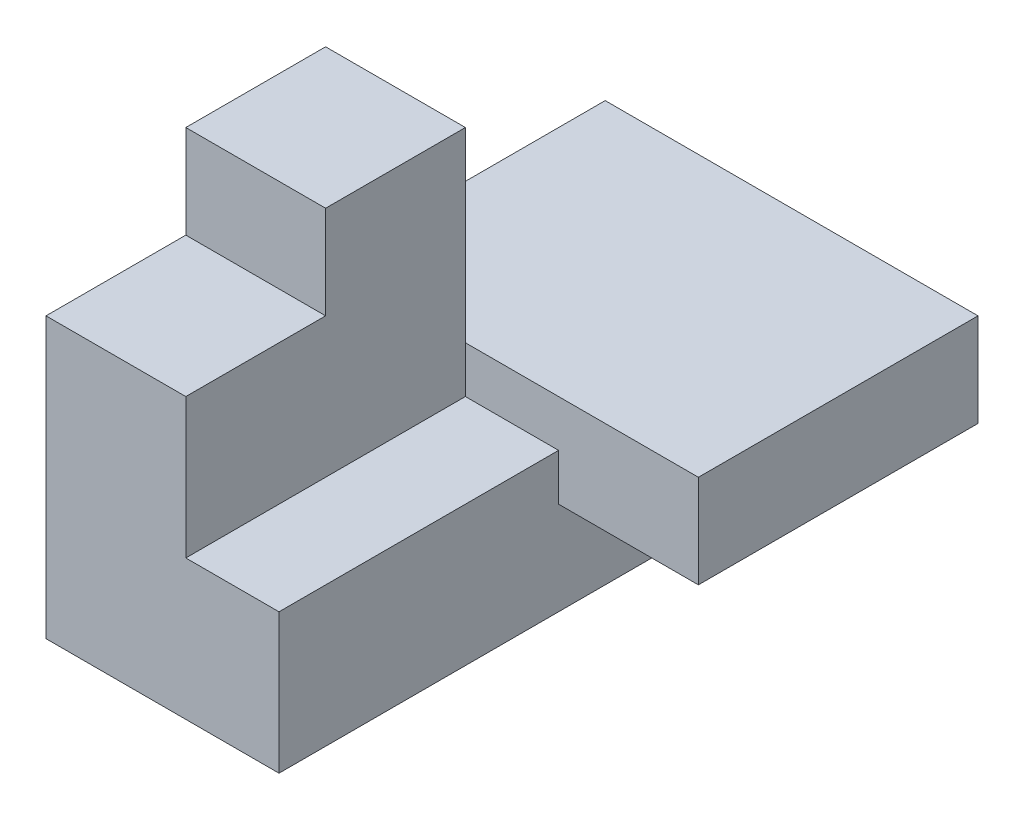
SolidWorks part; units mm, degrees
ref_plane "Front Plane" through (0, 0, 0) normal (0, 0, 1) x (1, 0, 0)
ref_plane "Top Plane" through (0, 0, 0) normal (0, 1, 0) x (1, 0, 0)
ref_plane "Right Plane" through (0, 0, 0) normal (1, 0, 0) x (0, 0, -1)
sketch "Sketch1" plane through (0, 0, 0) normal (0, 0, 1) x (1, 0, 0)
  line L1 (0, 0) -> (40, 0)
  line L2 (0, 0) -> (0, 40)
  line L3 (0, 40) -> (40, 40)
  line L4 (40, 0) -> (40, 40)
  dimension "D1" = 40
  dimension "D2" = 40
extrude "Boss-Extrude1" add sketch "Sketch1" along normal blind 60
sketch "Sketch2" plane through (0, 0, 60) normal (0, 0, 1) x (1, 0, 0)
  line L0 (0, 0) -> (40, 0) construction
  line L1 (40, 40) -> (20, 40)
  line L2 (40, 40) -> (40, 0)
  line L3 (40, 0) -> (20, 0)
  line L4 (20, 40) -> (20, 0)
extrude "Cut-Extrude1" cut sketch "Sketch2" against normal blind 30
sketch "Sketch3" plane through (40, 0, 0) normal (1, 0, 0) x (0, 0, -1)
  line L0 (0, 0) -> (0, 40) construction
  line L1 (-30, 0) -> (0, 0)
  line L2 (-30, 0) -> (-30, 20)
  line L3 (-30, 20) -> (0, 20)
  line L4 (0, 0) -> (0, 20)
sketch "Sketch4" plane through (0, 40, 0) normal (0, 1, 0) x (1, 0, 0)
  line L0 (0, -60) -> (0, 0) construction
  line L1 (40, 0) -> (0, 0)
  line L2 (40, 0) -> (40, -30)
  line L3 (40, -30) -> (0, -30)
  line L4 (0, 0) -> (0, -30)
extrude "Cut-Extrude2" cut sketch "Sketch4" against normal blind 20
sketch "Sketch5" plane through (40, 0, 0) normal (1, 0, 0) x (0, 0, -1)
  line L0 (-30, 0) -> (-30, 20) construction
  line L1 (0, 0) -> (-30, 0)
  line L2 (0, 0) -> (0, 10)
  line L3 (0, 10) -> (-30, 10)
  line L4 (-30, 0) -> (-30, 10)
extrude "Cut-Extrude3" cut sketch "Sketch5" against normal blind 15
sketch "Sketch6" plane through (20, 0, 0) normal (1, 0, 0) x (0, 0, -1)
  line L1 (-60, 40) -> (-45, 40)
  line L2 (-60, 40) -> (-60, 30)
  line L3 (-60, 30) -> (-45, 30)
  line L4 (-45, 40) -> (-45, 30)
extrude "Cut-Extrude4" cut sketch "Sketch6" against normal blind 25
sketch "Sketch8" plane through (20, 0, 0) normal (1, 0, 0) x (0, 0, -1)
  line L0 (-30, 0) -> (-30, 20) construction
  line L1 (-60, 0) -> (-30, 0)
  line L2 (-60, 0) -> (-60, 15)
  line L3 (-60, 15) -> (-30, 15)
  line L4 (-30, 0) -> (-30, 15)
  dimension "D1" = 15
extrude "Boss-Extrude2" add sketch "Sketch8" along normal blind 10
sketch "Sketch10" plane through (20, 0, 0) normal (1, 0, 0) x (0, 0, -1)
  line L1 (-60, 15) -> (-30, 15)
  line L2 (-60, 15) -> (-60, 40)
  line L3 (-60, 40) -> (-30, 40)
  line L4 (-30, 15) -> (-30, 40)
extrude "Cut-Extrude5" cut sketch "Sketch10" against normal blind 5
sketch "Sketch11" plane through (30, 0, 0) normal (1, 0, 0) x (0, 0, -1)
  line L1 (-30, 15) -> (-60, 15)
  line L2 (-30, 15) -> (-30, 0)
  line L3 (-30, 0) -> (-60, 0)
  line L4 (-60, 15) -> (-60, 0)
extrude "Cut-Extrude6" cut sketch "Sketch11" against normal blind 5
